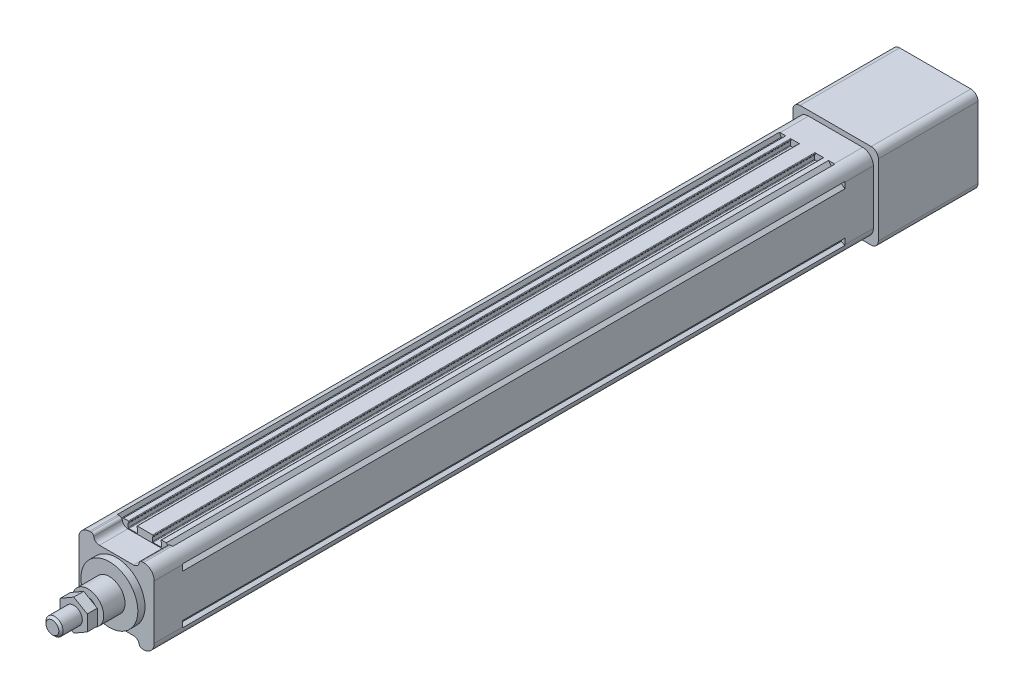
SolidWorks part; units mm, degrees
ref_plane "Front" through (0, 0, 0) normal (0, 0, 1) x (1, 0, 0)
ref_plane "Top" through (0, 0, 0) normal (0, 1, 0) x (1, 0, 0)
ref_plane "Right" through (0, 0, 0) normal (1, 0, 0) x (0, 0, -1)
sketch "草图1" plane through (0, 0, 0) normal (0, 0, 1) x (1, 0, 0)
  line L0 (19.7737, 3) -> (23.3, 3)
  line L1 (23.3, 3) -> (23.3, -3)
  line L2 (23.3, -3) -> (19.7737, -3)
  line L3 (-19.7737, -3) -> (-23.3, -3)
  line L4 (-23.3, -3) -> (-23.3, 3)
  line L5 (-23.3, 3) -> (-19.7737, 3)
  line L6 (-18.2, 24) -> (-19.4434, 26.4869)
  line L7 (-26.4869, 19.4434) -> (-24, 18.2)
  line L8 (-24, 18.2) -> (-24, 17.1)
  line L9 (-24, 17.1) -> (-26.5, 15)
  line L10 (-26.5, 15) -> (-26.5, -15)
  line L11 (-26.5, -15) -> (-24, -17.1)
  line L12 (-24, -17.1) -> (-24, -18.2)
  line L13 (-24, -18.2) -> (-26.4869, -19.4434)
  line L14 (-19.4434, -26.4869) -> (-18.2, -24)
  line L15 (-18.2, -24) -> (-17.1, -24)
  line L16 (-17.1, -24) -> (-15, -26.5)
  line L17 (-15, -26.5) -> (-11.65, -26.5)
  line L18 (-11.25, -26.1) -> (-11.25, -25.6)
  line L19 (-11.65, -25.2) -> (-11.75, -25.2)
  line L20 (-11.75, -25.2) -> (-11.75, -22.4)
  line L21 (-11.35, -22) -> (-5.65, -22)
  line L22 (-5.25, -22.4) -> (-5.25, -25.2)
  line L23 (-5.25, -25.2) -> (-5.35, -25.2)
  line L24 (-5.75, -25.6) -> (-5.75, -26.1)
  line L25 (-5.35, -26.5) -> (5.35, -26.5)
  line L26 (5.75, -26.1) -> (5.75, -25.6)
  line L27 (5.35, -25.2) -> (5.25, -25.2)
  line L28 (5.25, -25.2) -> (5.25, -22.4)
  line L29 (5.65, -22) -> (11.35, -22)
  line L30 (11.75, -22.4) -> (11.75, -25.2)
  line L31 (11.75, -25.2) -> (11.65, -25.2)
  line L32 (11.25, -25.6) -> (11.25, -26.1)
  line L33 (11.65, -26.5) -> (15, -26.5)
  line L34 (15, -26.5) -> (17.1, -24)
  line L35 (17.1, -24) -> (18.2, -24)
  line L36 (18.2, -24) -> (19.4434, -26.4869)
  line L37 (26.4869, -19.4434) -> (24, -18.2)
  line L38 (24, -18.2) -> (24, -17.1)
  line L39 (24, -17.1) -> (26.5, -15)
  line L40 (26.5, -15) -> (26.5, 15)
  line L41 (26.5, 15) -> (24, 17.1)
  line L42 (24, 17.1) -> (24, 18.2)
  line L43 (24, 18.2) -> (26.4869, 19.4434)
  line L44 (19.4434, 26.4869) -> (18.2, 24)
  line L45 (18.2, 24) -> (17.1, 24)
  line L46 (17.1, 24) -> (15, 26.5)
  line L47 (15, 26.5) -> (11.65, 26.5)
  line L48 (11.25, 26.1) -> (11.25, 25.6)
  line L49 (11.65, 25.2) -> (11.75, 25.2)
  line L50 (11.75, 25.2) -> (11.75, 22.4)
  line L51 (11.35, 22) -> (5.65, 22)
  line L52 (5.25, 22.4) -> (5.25, 25.2)
  line L53 (5.25, 25.2) -> (5.35, 25.2)
  line L54 (5.75, 25.6) -> (5.75, 26.1)
  line L55 (5.35, 26.5) -> (-5.35, 26.5)
  line L56 (-5.75, 26.1) -> (-5.75, 25.6)
  line L57 (-5.35, 25.2) -> (-5.25, 25.2)
  line L58 (-5.25, 25.2) -> (-5.25, 22.4)
  line L59 (-5.65, 22) -> (-11.35, 22)
  line L60 (-11.75, 22.4) -> (-11.75, 25.2)
  line L61 (-11.75, 25.2) -> (-11.65, 25.2)
  line L62 (-11.25, 25.6) -> (-11.25, 26.1)
  line L63 (-11.65, 26.5) -> (-15, 26.5)
  line L64 (-15, 26.5) -> (-17.1, 24)
  line L65 (-17.1, 24) -> (-18.2, 24)
  arc A0 (19.7737, 3) -> (-19.7737, 3) centre (0, 0) ccw
  arc A1 (-19.7737, -3) -> (19.7737, -3) centre (0, 0) ccw
  circle A2 centre (19, 19) radius 2.1
  circle A3 centre (19, -19) radius 2.1
  circle A4 centre (-19, -19) radius 2.1
  circle A5 centre (-19, 19) radius 2.1
  arc A6 (-19.4434, 26.4869) -> (-26.4869, 19.4434) centre (-19, 19) ccw
  arc A7 (-26.4869, -19.4434) -> (-19.4434, -26.4869) centre (-19, -19) ccw
  arc A8 (-11.65, -26.5) -> (-11.25, -26.1) centre (-11.65, -26.1) ccw
  arc A9 (-11.25, -25.6) -> (-11.65, -25.2) centre (-11.65, -25.6) ccw
  arc A10 (-11.35, -22) -> (-11.75, -22.4) centre (-11.35, -22.4) ccw
  arc A11 (-5.25, -22.4) -> (-5.65, -22) centre (-5.65, -22.4) ccw
  arc A12 (-5.35, -25.2) -> (-5.75, -25.6) centre (-5.35, -25.6) ccw
  arc A13 (-5.75, -26.1) -> (-5.35, -26.5) centre (-5.35, -26.1) ccw
  arc A14 (5.35, -26.5) -> (5.75, -26.1) centre (5.35, -26.1) ccw
  arc A15 (5.75, -25.6) -> (5.35, -25.2) centre (5.35, -25.6) ccw
  arc A16 (5.65, -22) -> (5.25, -22.4) centre (5.65, -22.4) ccw
  arc A17 (11.75, -22.4) -> (11.35, -22) centre (11.35, -22.4) ccw
  arc A18 (11.65, -25.2) -> (11.25, -25.6) centre (11.65, -25.6) ccw
  arc A19 (11.25, -26.1) -> (11.65, -26.5) centre (11.65, -26.1) ccw
  arc A20 (19.4434, -26.4869) -> (26.4869, -19.4434) centre (19, -19) ccw
  arc A21 (26.4869, 19.4434) -> (19.4434, 26.4869) centre (19, 19) ccw
  arc A22 (11.65, 26.5) -> (11.25, 26.1) centre (11.65, 26.1) ccw
  arc A23 (11.25, 25.6) -> (11.65, 25.2) centre (11.65, 25.6) ccw
  arc A24 (11.35, 22) -> (11.75, 22.4) centre (11.35, 22.4) ccw
  arc A25 (5.25, 22.4) -> (5.65, 22) centre (5.65, 22.4) ccw
  arc A26 (5.35, 25.2) -> (5.75, 25.6) centre (5.35, 25.6) ccw
  arc A27 (5.75, 26.1) -> (5.35, 26.5) centre (5.35, 26.1) ccw
  arc A28 (-5.35, 26.5) -> (-5.75, 26.1) centre (-5.35, 26.1) ccw
  arc A29 (-5.75, 25.6) -> (-5.35, 25.2) centre (-5.35, 25.6) ccw
  arc A30 (-5.65, 22) -> (-5.25, 22.4) centre (-5.65, 22.4) ccw
  arc A31 (-11.75, 22.4) -> (-11.35, 22) centre (-11.35, 22.4) ccw
  arc A32 (-11.65, 25.2) -> (-11.25, 25.6) centre (-11.65, 25.6) ccw
  arc A33 (-11.25, 26.1) -> (-11.65, 26.5) centre (-11.65, 26.1) ccw
extrude "凸台-拉伸1" add sketch "草图1" along normal blind 465
sketch "草图6" plane through (0, 0, 465) normal (0, 0, 1) x (1, 0, 0)
  line L0 (0, 0) -> (19, 0) construction
  line L2 (-26.5, -19) -> (-26.5, 19)
  line L3 (-19, 26.5) -> (-17.9161, 26.5)
  line L4 (26.5, -19) -> (26.5, 19)
  line L5 (-26.5, -26.5) -> (26.5, 26.5) construction
  line L6 (-26.5, 26.5) -> (26.5, -26.5) construction
  line L7 (-12, 21.5) -> (12, 21.5)
  line L9 (19, 26.5) -> (17.9161, 26.5)
  line L10 (19, -26.5) -> (17.9161, -26.5)
  line L11 (-12, -21.5) -> (12, -21.5)
  line L12 (-19, -26.5) -> (-17.9161, -26.5)
  arc A0 (12, 21.5) -> (15.9441, 24.8333) centre (12, 25.5) ccw
  arc A1 (-15.9441, 24.8333) -> (-12, 21.5) centre (-12, 25.5) ccw
  arc A2 (-15.9441, 24.8333) -> (-17.9161, 26.5) centre (-17.9161, 24.5) ccw
  arc A3 (15.9441, 24.8333) -> (17.9161, 26.5) centre (17.9161, 24.5) cw
  arc A4 (-26.5, -19) -> (-19, -26.5) centre (-19, -19) ccw
  arc A5 (19, -26.5) -> (26.5, -19) centre (19, -19) ccw
  arc A6 (26.5, 19) -> (19, 26.5) centre (19, 19) ccw
  arc A7 (-26.5, 19) -> (-19, 26.5) centre (-19, 19) cw
  arc A8 (15.9441, -24.8333) -> (17.9161, -26.5) centre (17.9161, -24.5) ccw
  arc A9 (12, -21.5) -> (15.9441, -24.8333) centre (12, -25.5) cw
  arc A10 (-15.9441, -24.8333) -> (-12, -21.5) centre (-12, -25.5) cw
  arc A11 (-15.9441, -24.8333) -> (-17.9161, -26.5) centre (-17.9161, -24.5) cw
  point P0 (0, 0)
  point P9 (0, 21.5)
  point P13 (20, 20.8461)
  point P16 (-12, 20.8461)
  dimension "D5" = 4
  dimension "D6" = 2
  dimension "D7" = 2
  dimension "D9" = 7.5
  dimension "D1" = 53
  dimension "D2" = 53
  dimension "D3" = 26.5
  dimension "D4" = 24
  dimension "D8" = 5
extrude "凸台-拉伸2" add sketch "草图6" along normal blind 20
sketch "草图7" plane through (0, 0, 485) normal (0, 0, 1) x (1, 0, 0)
  circle A0 centre (0, 0) radius 20
  dimension "D1" = 40
extrude "凸台-拉伸3" add sketch "草图7" along normal blind 5
sketch "草图9" plane through (0, 0, 490) normal (0, 0, 1) x (1, 0, 0)
  circle A0 centre (0, 0) radius 11
  dimension "D1" = 22
extrude "凸台-拉伸4" add sketch "草图9" along normal blind 15
sketch "草图10" plane through (0, 0, 505) normal (0, 0, 1) x (1, 0, 0)
  circle A0 centre (0, 0) radius 6
  dimension "D1" = 12
extrude "凸台-拉伸5" add sketch "草图10" along normal blind 25
sketch "草图11" plane through (0, 0, 0) normal (0, 0, -1) x (-1, 0, 0)
  line L1 (-19, -26.5) -> (19, -26.5)
  line L2 (-26.5, -19) -> (-26.5, 19)
  line L3 (-19, 26.5) -> (19, 26.5)
  line L4 (26.5, -19) -> (26.5, 19)
  line L5 (-26.5, -26.5) -> (26.5, 26.5) construction
  line L6 (-26.5, 26.5) -> (26.5, -26.5) construction
  arc A0 (-26.5, -19) -> (-19, -26.5) centre (-19, -19) ccw
  arc A1 (19, -26.5) -> (26.5, -19) centre (19, -19) ccw
  arc A2 (26.5, 19) -> (19, 26.5) centre (19, 19) ccw
  arc A3 (-26.5, 19) -> (-19, 26.5) centre (-19, 19) cw
  point P0 (0, 0)
  dimension "D3" = 7.5
  dimension "D1" = 53
  dimension "D2" = 53
extrude "凸台-拉伸6" add sketch "草图11" along normal blind 20
sketch "草图12" plane through (0, 0, -20) normal (0, 0, -1) x (-1, 0, 0)
  line L1 (-25, -30) -> (25, -30)
  line L2 (-30, -25) -> (-30, 25)
  line L3 (-25, 30) -> (25, 30)
  line L4 (30, -25) -> (30, 25)
  line L5 (-30, -30) -> (30, 30) construction
  line L6 (-30, 30) -> (30, -30) construction
  arc A0 (-30, -25) -> (-25, -30) centre (-25, -25) ccw
  arc A1 (25, -30) -> (30, -25) centre (25, -25) ccw
  arc A2 (30, 25) -> (25, 30) centre (25, 25) ccw
  arc A3 (-30, 25) -> (-25, 30) centre (-25, 25) cw
  point P0 (0, 0)
  dimension "D3" = 5
  dimension "D1" = 60
  dimension "D2" = 60
extrude "凸台-拉伸7" add sketch "草图12" along normal blind 70
sketch "草图14" plane through (0, 0, -90) normal (0, 0, -1) x (-1, 0, 0)
  circle A0 centre (0, 0) radius 19
  dimension "D1" = 38
extrude "切除-拉伸2" cut sketch "草图14" against normal blind 70
hole_wizard "M6 螺纹孔1" positions "草图15" profile "草图16" tap size "M6" standard "GB"
sketch "草图15" plane through (-26.5, 0, 0) normal (-1, 0, 0) x (0, 0, 1)
  line L0 (-20, -25) -> (-20, 25) construction
  line L1 (485, 19) -> (485, -19) construction
  point P0 (475, 11)
  point P2 (475, -11)
  point P4 (-10, 11)
  point P6 (-10, -11)
  dimension "D1" = 10
  dimension "D2" = 10
  dimension "D3" = 11
  dimension "D4" = 11
  dimension "D5" = 10
  dimension "D6" = 10
  dimension "D7" = 22
  dimension "D8" = 11
sketch "草图16" plane through (-26.5, 11, 475) normal (0, 1, 0) x (0, 0, 1)
  line L0 (0, 0) -> (0, 16.5022)
  line L1 (0, 16.5022) -> (2.5, 15)
  line L2 (2.5, 15) -> (2.5, 0)
  line L5 (2.5, 0) -> (0, 0)
  line L10 (0, 16.5022) -> (-2.5, 15) construction
  line L11 (0, -6.35) -> (0, 107.95) construction
  dimension "螺纹孔钻头直径" = 5
  dimension "螺纹孔钻头深度" = 15
  dimension "导头角度" = 118
cosmetic thread "孔螺蚊线4" parameters "D1"=12, "D2"=6
cosmetic thread "孔螺蚊线5" parameters "D1"=12, "D2"=6
cosmetic thread "孔螺蚊线6" parameters "D1"=12, "D2"=6
cosmetic thread "孔螺蚊线7" parameters "D1"=12, "D2"=6
chamfer "倒角1" distance 1.5 angle 45 1 edges at (6, 0, 530)
sketch "草图17" plane through (0, 0, 505) normal (0, 0, 1) x (1, 0, 0)
  line L1 (0, 10.9697) -> (-9.5, 5.4848)
  line L2 (-9.5, 5.4848) -> (-9.5, -5.4848)
  line L3 (-9.5, -5.4848) -> (0, -10.9697)
  line L4 (0, -10.9697) -> (9.5, -5.4848)
  line L5 (9.5, -5.4848) -> (9.5, 5.4848)
  line L6 (9.5, 5.4848) -> (0, 10.9697)
  circle A0 centre (0, 0) radius 9.5 construction
  dimension "D1" = 19
extrude "凸台-拉伸8" add sketch "草图17" along normal blind 7 from offset 3
